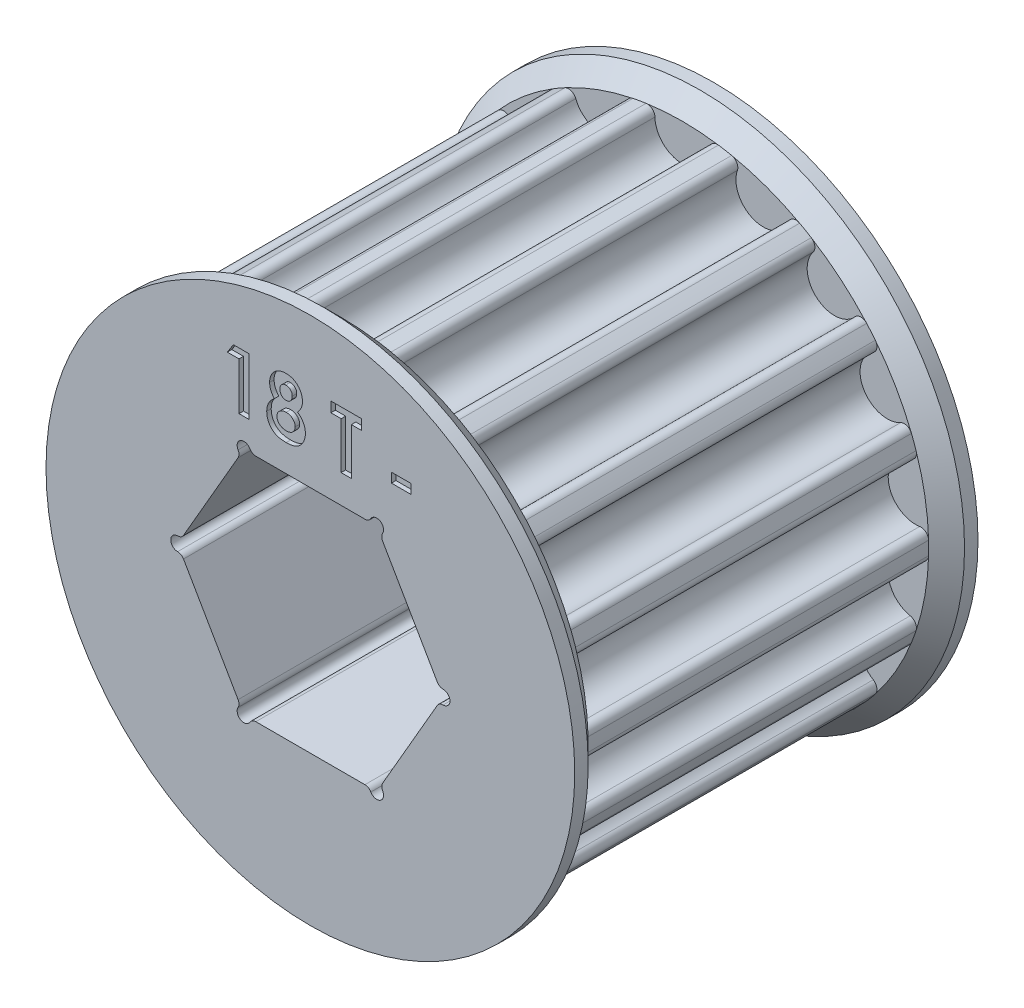
SolidWorks part; units mm, degrees
material "Nailon 6/10"
ref_plane "Alzado" through (0, 0, 0) normal (0, 0, 1) x (1, 0, 0)
ref_plane "Planta" through (0, 0, 0) normal (0, 1, 0) x (1, 0, 0)
ref_plane "Vista lateral" through (0, 0, 0) normal (1, 0, 0) x (0, 0, -1)
sketch "Croquis3" plane through (0, 0, 0) normal (0, 0, 1) x (1, 0, 0)
  line L0 (0, 0) -> (0, 13.75) construction
  line L1 (0, 0) -> (4.7028, 12.9208) construction
  circle A0 centre (0, 0) radius 13.75 construction
  circle A1 centre (0, 0) radius 11.69 construction
  circle A2 centre (0, 13.215) radius 1.525 construction
  circle A3 centre (1.9546, 13.1758) radius 0.43 construction
  circle A4 centre (4.5198, 12.418) radius 1.525 construction
  circle A5 centre (2.6697, 13.0497) radius 0.43 construction
  arc A6 (0, 11.69) -> (1.5247, 13.1844) centre (0, 13.215) ccw
  arc A7 (1.5247, 13.1844) -> (2.0177, 13.6012) centre (1.9546, 13.1758) cw
  arc A8 (2.0177, 13.6012) -> (2.7558, 13.471) centre (0, 0) cw
  arc A9 (2.7558, 13.471) -> (3.0766, 12.9108) centre (2.6697, 13.0497) cw
  arc A10 (3.0766, 12.9108) -> (3.9982, 10.985) centre (4.5198, 12.418) ccw
  arc A11 (7.3068, 11.0799) -> (7.5142, 8.9551) centre (8.4944, 10.1233) ccw
  arc A12 (7.197, 11.716) -> (7.3068, 11.0799) centre (6.9719, 11.3497) cw
  arc A13 (6.5479, 12.0908) -> (7.197, 11.716) centre (0, 0) cw
  arc A14 (5.9421, 11.8678) -> (6.5479, 12.0908) centre (6.3431, 11.7127) cw
  arc A15 (3.9982, 10.985) -> (5.9421, 11.8678) centre (4.5198, 12.418) ccw
  arc A16 (10.6557, 7.9126) -> (10.1238, 5.845) centre (11.4445, 6.6075) ccw
  arc A17 (10.7701, 8.548) -> (10.6557, 7.9126) centre (10.4333, 8.2806) cw
  arc A18 (10.2883, 9.1221) -> (10.7701, 8.548) centre (0, 0) cw
  arc A19 (9.6428, 9.1198) -> (10.2883, 9.1221) centre (9.9666, 8.8369) cw
  arc A20 (7.5142, 8.9551) -> (9.6428, 9.1198) centre (8.4944, 10.1233) ccw
  arc A21 (12.7194, 3.791) -> (11.5124, 2.0299) centre (13.0142, 2.2948) ccw
  arc A22 (13.0441, 4.3489) -> (12.7194, 3.791) centre (12.6362, 4.2129) cw
  arc A23 (12.7878, 5.0532) -> (13.0441, 4.3489) centre (0, 0) cw
  arc A24 (12.1804, 5.2718) -> (12.7878, 5.0532) centre (12.3879, 4.8952) cw
  arc A25 (10.1238, 5.845) -> (12.1804, 5.2718) centre (11.4445, 6.6075) ccw
  arc A26 (13.2489, -0.7879) -> (11.5124, -2.0299) centre (13.0142, -2.2948) ccw
  arc A27 (13.7449, -0.3748) -> (13.2489, -0.7879) centre (13.3151, -0.363) cw
  arc A28 (13.7449, 0.3748) -> (13.7449, -0.3748) centre (0, 0) cw
  arc A29 (13.2489, 0.7879) -> (13.7449, 0.3748) centre (13.3151, 0.363) cw
  arc A30 (11.5124, 2.0299) -> (13.2489, 0.7879) centre (13.0142, 2.2948) ccw
  arc A31 (12.1804, -5.2718) -> (10.1238, -5.845) centre (11.4445, -6.6075) ccw
  arc A32 (12.7878, -5.0532) -> (12.1804, -5.2718) centre (12.3879, -4.8952) cw
  arc A33 (13.0441, -4.3489) -> (12.7878, -5.0532) centre (0, 0) cw
  arc A34 (12.7194, -3.791) -> (13.0441, -4.3489) centre (12.6362, -4.2129) cw
  arc A35 (11.5124, -2.0299) -> (12.7194, -3.791) centre (13.0142, -2.2948) ccw
  arc A36 (9.6428, -9.1198) -> (7.5142, -8.9551) centre (8.4944, -10.1233) ccw
  arc A37 (10.2883, -9.1221) -> (9.6428, -9.1198) centre (9.9666, -8.8369) cw
  arc A38 (10.7701, -8.548) -> (10.2883, -9.1221) centre (0, 0) cw
  arc A39 (10.6557, -7.9126) -> (10.7701, -8.548) centre (10.4333, -8.2806) cw
  arc A40 (10.1238, -5.845) -> (10.6557, -7.9126) centre (11.4445, -6.6075) ccw
  arc A41 (5.9421, -11.8678) -> (3.9982, -10.985) centre (4.5198, -12.418) ccw
  arc A42 (6.5479, -12.0908) -> (5.9421, -11.8678) centre (6.3431, -11.7127) cw
  arc A43 (7.197, -11.716) -> (6.5479, -12.0908) centre (0, 0) cw
  arc A44 (7.3068, -11.0799) -> (7.197, -11.716) centre (6.9719, -11.3497) cw
  arc A45 (7.5142, -8.9551) -> (7.3068, -11.0799) centre (8.4944, -10.1233) ccw
  arc A46 (1.5247, -13.1844) -> (0, -11.69) centre (0, -13.215) ccw
  arc A47 (2.0177, -13.6012) -> (1.5247, -13.1844) centre (1.9546, -13.1758) cw
  arc A48 (2.7558, -13.471) -> (2.0177, -13.6012) centre (0, 0) cw
  arc A49 (3.0766, -12.9108) -> (2.7558, -13.471) centre (2.6697, -13.0497) cw
  arc A50 (3.9982, -10.985) -> (3.0766, -12.9108) centre (4.5198, -12.418) ccw
  arc A51 (-3.0766, -12.9108) -> (-3.9982, -10.985) centre (-4.5198, -12.418) ccw
  arc A52 (-2.7558, -13.471) -> (-3.0766, -12.9108) centre (-2.6697, -13.0497) cw
  arc A53 (-2.0177, -13.6012) -> (-2.7558, -13.471) centre (0, 0) cw
  arc A54 (-1.5247, -13.1844) -> (-2.0177, -13.6012) centre (-1.9546, -13.1758) cw
  arc A55 (0, -11.69) -> (-1.5247, -13.1844) centre (0, -13.215) ccw
  arc A56 (-7.3068, -11.0799) -> (-7.5142, -8.9551) centre (-8.4944, -10.1233) ccw
  arc A57 (-7.197, -11.716) -> (-7.3068, -11.0799) centre (-6.9719, -11.3497) cw
  arc A58 (-6.5479, -12.0908) -> (-7.197, -11.716) centre (0, 0) cw
  arc A59 (-5.9421, -11.8678) -> (-6.5479, -12.0908) centre (-6.3431, -11.7127) cw
  arc A60 (-3.9982, -10.985) -> (-5.9421, -11.8678) centre (-4.5198, -12.418) ccw
  arc A61 (-10.6557, -7.9126) -> (-10.1238, -5.845) centre (-11.4445, -6.6075) ccw
  arc A62 (-10.7701, -8.548) -> (-10.6557, -7.9126) centre (-10.4333, -8.2806) cw
  arc A63 (-10.2883, -9.1221) -> (-10.7701, -8.548) centre (0, 0) cw
  arc A64 (-9.6428, -9.1198) -> (-10.2883, -9.1221) centre (-9.9666, -8.8369) cw
  arc A65 (-7.5142, -8.9551) -> (-9.6428, -9.1198) centre (-8.4944, -10.1233) ccw
  arc A66 (-12.7194, -3.791) -> (-11.5124, -2.0299) centre (-13.0142, -2.2948) ccw
  arc A67 (-13.0441, -4.3489) -> (-12.7194, -3.791) centre (-12.6362, -4.2129) cw
  arc A68 (-12.7878, -5.0532) -> (-13.0441, -4.3489) centre (0, 0) cw
  arc A69 (-12.1804, -5.2718) -> (-12.7878, -5.0532) centre (-12.3879, -4.8952) cw
  arc A70 (-10.1238, -5.845) -> (-12.1804, -5.2718) centre (-11.4445, -6.6075) ccw
  arc A71 (-13.2489, 0.7879) -> (-11.5124, 2.0299) centre (-13.0142, 2.2948) ccw
  arc A72 (-13.7449, 0.3748) -> (-13.2489, 0.7879) centre (-13.3151, 0.363) cw
  arc A73 (-13.7449, -0.3748) -> (-13.7449, 0.3748) centre (0, 0) cw
  arc A74 (-13.2489, -0.7879) -> (-13.7449, -0.3748) centre (-13.3151, -0.363) cw
  arc A75 (-11.5124, -2.0299) -> (-13.2489, -0.7879) centre (-13.0142, -2.2948) ccw
  arc A76 (-12.1804, 5.2718) -> (-10.1238, 5.845) centre (-11.4445, 6.6075) ccw
  arc A77 (-12.7878, 5.0532) -> (-12.1804, 5.2718) centre (-12.3879, 4.8952) cw
  arc A78 (-13.0441, 4.3489) -> (-12.7878, 5.0532) centre (0, 0) cw
  arc A79 (-12.7194, 3.791) -> (-13.0441, 4.3489) centre (-12.6362, 4.2129) cw
  arc A80 (-11.5124, 2.0299) -> (-12.7194, 3.791) centre (-13.0142, 2.2948) ccw
  arc A81 (-9.6428, 9.1198) -> (-7.5142, 8.9551) centre (-8.4944, 10.1233) ccw
  arc A82 (-10.2883, 9.1221) -> (-9.6428, 9.1198) centre (-9.9666, 8.8369) cw
  arc A83 (-10.7701, 8.548) -> (-10.2883, 9.1221) centre (0, 0) cw
  arc A84 (-10.6557, 7.9126) -> (-10.7701, 8.548) centre (-10.4333, 8.2806) cw
  arc A85 (-10.1238, 5.845) -> (-10.6557, 7.9126) centre (-11.4445, 6.6075) ccw
  arc A86 (-5.9421, 11.8678) -> (-3.9982, 10.985) centre (-4.5198, 12.418) ccw
  arc A87 (-6.5479, 12.0908) -> (-5.9421, 11.8678) centre (-6.3431, 11.7127) cw
  arc A88 (-7.197, 11.716) -> (-6.5479, 12.0908) centre (0, 0) cw
  arc A89 (-7.3068, 11.0799) -> (-7.197, 11.716) centre (-6.9719, 11.3497) cw
  arc A90 (-7.5142, 8.9551) -> (-7.3068, 11.0799) centre (-8.4944, 10.1233) ccw
  arc A91 (-1.5247, 13.1844) -> (0, 11.69) centre (0, 13.215) ccw
  arc A92 (-2.0177, 13.6012) -> (-1.5247, 13.1844) centre (-1.9546, 13.1758) cw
  arc A93 (-2.7558, 13.471) -> (-2.0177, 13.6012) centre (0, 0) cw
  arc A94 (-3.0766, 12.9108) -> (-2.7558, 13.471) centre (-2.6697, 13.0497) cw
  arc A95 (-3.9982, 10.985) -> (-3.0766, 12.9108) centre (-4.5198, 12.418) ccw
  dimension "D1" = 27.5
  dimension "D2" = 23.38
  dimension "D3" = 3.05
  dimension "D4" = 0.86
  dimension "D5" = 20
  dimension "D6" = 18
extrude "Saliente-Extruir1" add sketch "Croquis3" along normal mid plane 19 contours A65 A56 A57 A58 A59 A60 A51 A52 A53 A54 A55 A46 A47 A48 A49 A50 A41 A42 A43 A44 A45 A36 A37 A38 A39 A40 A31 A32 A33 A34 A35 A26 A27 A28 A29 A30 A21 A22 A23 A24 A25 A16 A17 A18 A19 A20 A11 A12 A13 A14 A15
sketch "Croquis5" plane through (0, 0, 9.5) normal (0, 0, 1) x (1, 0, 0)
  circle A0 centre (0, 0) radius 13.75
  arc A1 (2.7558, 13.471) -> (2.0177, 13.6012) centre (0, 0) ccw construction
extrude "Saliente-Extruir2" add sketch "Croquis5" along normal blind 1 draft 45 draft outward yes
sketch "Croquis7" plane through (0, 0, 10.5) normal (0, 0, 1) x (1, 0, 0)
  circle A0 centre (0, 0) radius 14.75 construction
  circle A1 centre (0, 0) radius 14.75
extrude "Saliente-Extruir3" add sketch "Croquis7" along normal blind 0.75
mirror "Simetría1" about plane through (0, 0, 0) normal (0, 0, 1) of "Saliente-Extruir3", "Saliente-Extruir2"
sketch "Croquis6" plane through (0, 0, 11.25) normal (0, 0, 1) x (1, 0, 0)
  line L5 (3.7037, -6.415) -> (7.4074, 0)
  line L6 (7.4074, 0) -> (3.7037, 6.415)
  line L7 (3.7037, 6.415) -> (-3.7037, 6.415)
  line L8 (-3.7037, 6.415) -> (-7.4074, 0)
  line L9 (-7.4074, 0) -> (-3.7037, -6.415)
  line L10 (-3.7037, -6.415) -> (3.7037, -6.415)
  circle A1 centre (0, 0) radius 6.415 construction
  arc A2 (-3.3227, 6.415) -> (-3.8942, 6.085) centre (-3.7037, 6.415) ccw
  arc A3 (3.8942, 6.085) -> (3.3227, 6.415) centre (3.7037, 6.415) ccw
  arc A4 (7.2169, -0.33) -> (7.2169, 0.33) centre (7.4074, 0) ccw
  arc A5 (3.3227, -6.415) -> (3.8942, -6.085) centre (3.7037, -6.415) ccw
  arc A6 (-3.8942, -6.085) -> (-3.3227, -6.415) centre (-3.7037, -6.415) ccw
  arc A7 (-7.2169, 0.33) -> (-7.2169, -0.33) centre (-7.4074, 0) ccw
  dimension "D1" = 12.83
  dimension "D2" = 0.381
  dimension "D3" = 6
extrude "Cortar-Extruir1" cut sketch "Croquis6" against normal through all contours L9 L10 L5 L6 L7 L8 | L7 A2 L8 | L6 A3 L7 | L5 A4 L6 | L10 A5 L5 | L9 A6 L10 | L8 A7 L9
fillet "Redondeo1" radius 0.381 12 edges at (-7.2169, 0.33, 0) (3.3227, -6.415, 0) (-3.3227, -6.415, 0) (-7.2169, -0.33, 0) (-3.8942, -6.085, 0) (7.2169, -0.33, 0) (3.8942, -6.085, 0) (7.2169, 0.33, 0) (3.8942, 6.085, 0) (3.3227, 6.415, 0) (-3.8942, 6.085, 0) (-3.3227, 6.415, 0)
sketch "Croquis9" plane through (0, 0, 0) normal (0, 0, 1) x (1, 0, 0)
  line L0 (-5, 8) -> (5, 8) construction
  text T0 "18 T - 15mm" font "Century Gothic" height 3.175
  point P2 (0, 8)
  dimension "D1" = 10
  dimension "D2" = 8
extrude "Cortar-Extruir3" cut sketch "Croquis9" against normal blind 0.25 from surface at 11.25 starting at face at (0, 0, 11.25)
equation "\"X\"=27.5"
equation "\"N\"=18"
equation "\"D1@Croquis3\"=\"X\""
equation "\"Y\"= \"X\" - 2 * 2.06"
equation "\"A\"= 360 / \"N\""
equation "\"D2@Croquis3\"=\"Y\""
equation "\"D5@Croquis3\"=\"A\""
equation "\"D6@Croquis3\"=\"N\""
equation "\"Grosor\" = 19"
equation "\"D1@Saliente-Extruir1\"=\"Grosor\""
